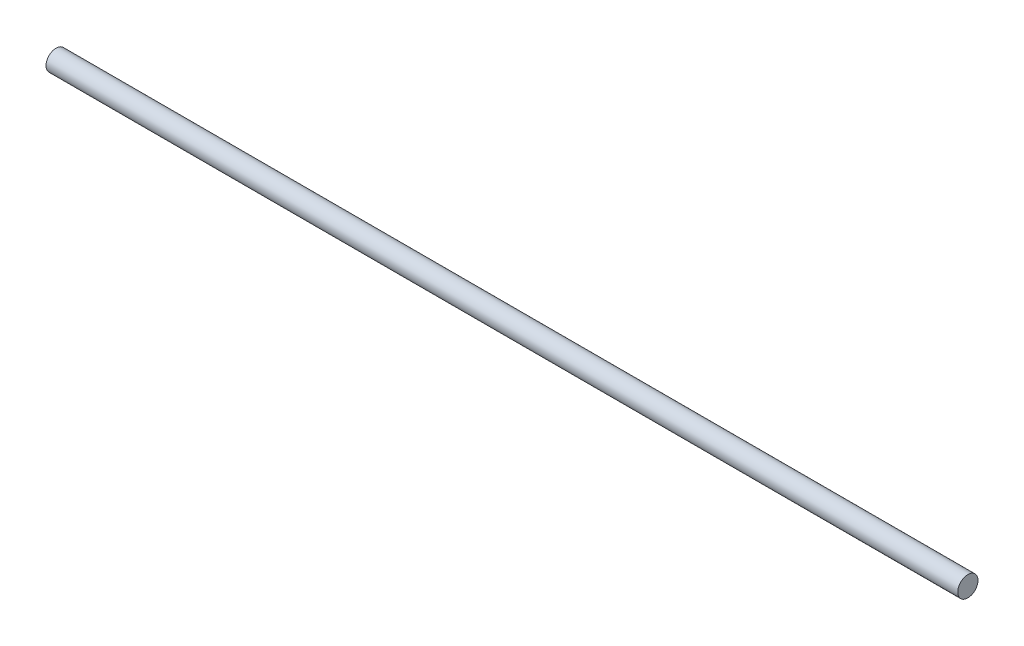
SolidWorks part; units mm, degrees
material "Hexcel AS4C (3000 Filaments)"
ref_plane "Front Plane" through (0, 0, 0) normal (0, 0, 1) x (1, 0, 0)
ref_plane "Top Plane" through (0, 0, 0) normal (0, 1, 0) x (1, 0, 0)
ref_plane "Right Plane" through (0, 0, 0) normal (1, 0, 0) x (0, 0, -1)
sketch "Sketch1" plane through (0, 0, 0) normal (1, 0, 0) x (0, 0, -1)
  circle A0 centre (0, 0) radius 5
  dimension "D1" = 10
extrude "Boss-Extrude1" add sketch "Sketch1" along normal mid plane 450
